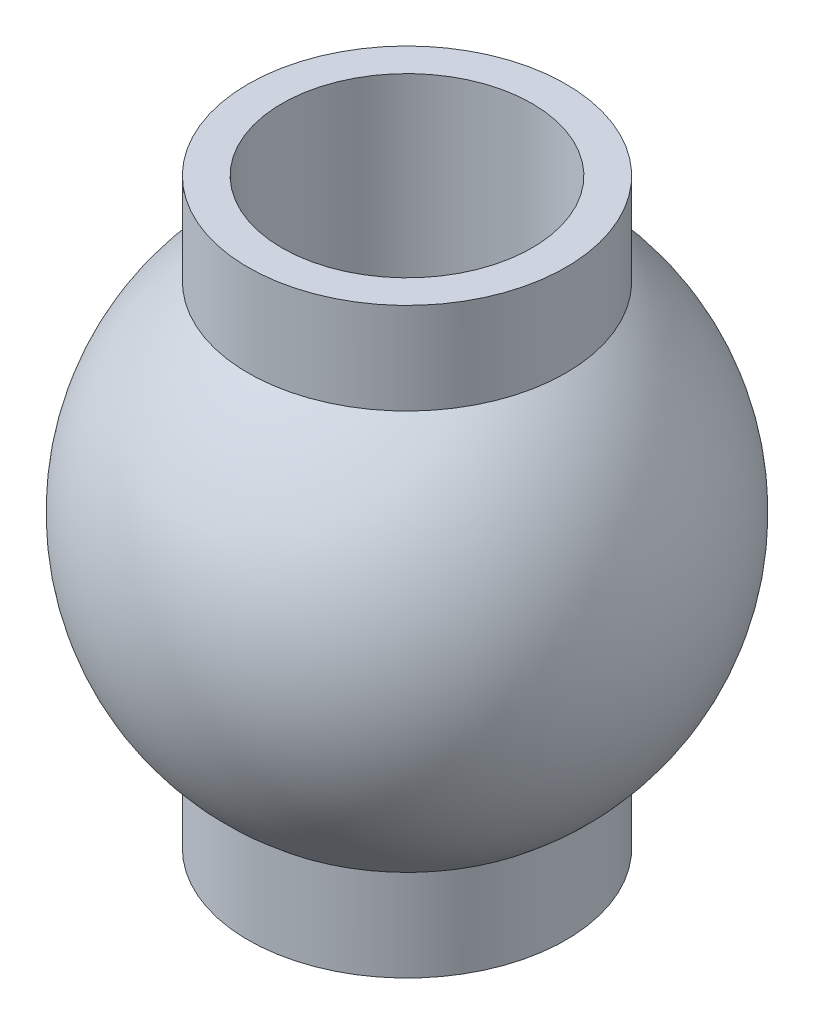
SolidWorks part; units mm, degrees
material "Brass"
ref_plane "Front Plane" through (0, 0, 0) normal (0, 0, 1) x (1, 0, 0)
ref_plane "Top Plane" through (0, 0, 0) normal (0, 1, 0) x (1, 0, 0)
ref_plane "Right Plane" through (0, 0, 0) normal (1, 0, 0) x (0, 0, -1)
sketch "Sketch1" plane through (0, 0, 0) normal (0, 0, 1) x (1, 0, 0)
  line L0 (0, 3.4925) -> (0, -3.4925)
  line L9 (-1.905, 3.4925) -> (1.905, 3.4925)
  line L10 (-1.905, 3.4925) -> (-1.905, 2.3956)
  line L15 (-1.905, 2.3956) -> (1.905, 2.3956)
  line L16 (1.905, 3.4925) -> (1.905, 2.3956)
  line L17 (-1.905, 3.4925) -> (1.905, 2.3956) construction
  line L18 (-1.905, 2.3956) -> (1.905, 3.4925) construction
  line L20 (-1.905, -2.3956) -> (1.905, -2.3956)
  line L21 (-1.905, -2.3956) -> (-1.905, -3.4925)
  line L22 (-1.905, -3.4925) -> (1.905, -3.4925)
  line L23 (1.905, -2.3956) -> (1.905, -3.4925)
  line L24 (-1.905, -2.3956) -> (1.905, -3.4925) construction
  line L25 (-1.905, -3.4925) -> (1.905, -2.3956) construction
  circle A6 centre (0, 0) radius 3.0607
  point P2 (0, 2.944)
  point P15 (0, -2.944)
  dimension "D2" = 3.81
  dimension "D1" = 6.1214
  dimension "D3" = 6.985
revolve "Revolve1" add sketch "Sketch1" angle 360 about L0
sketch "Sketch2" plane through (0, 0, 0) normal (0, 1, 0) x (1, 0, 0)
  circle A0 centre (0, 0) radius 1.5
  dimension "D1" = 3
extrude "Cut-Extrude1" cut sketch "Sketch2" against normal through all both and the other way through all
